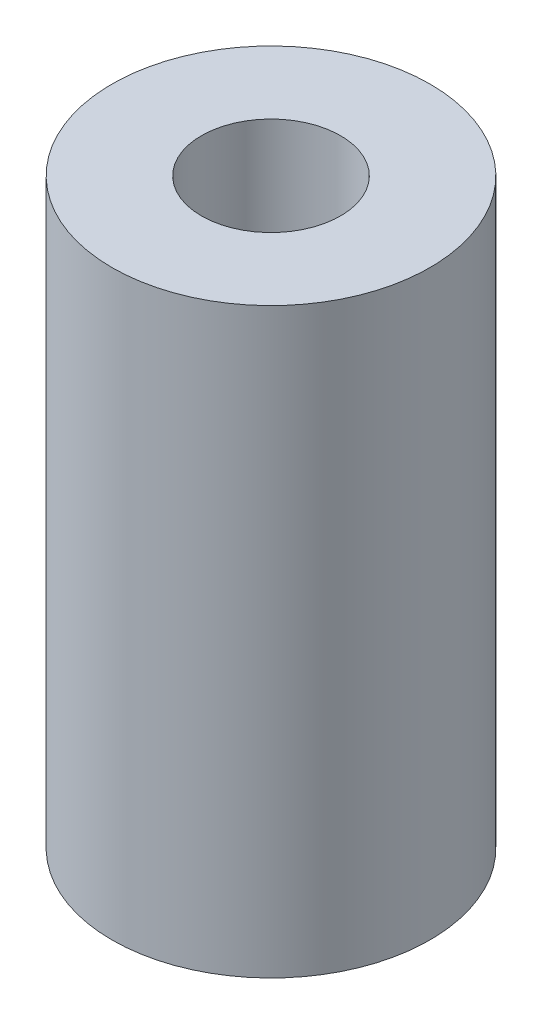
SolidWorks part; units mm, degrees
ref_plane "前视基准面" through (0, 0, 0) normal (0, 0, 1) x (1, 0, 0)
ref_plane "上视基准面" through (0, 0, 0) normal (0, 1, 0) x (1, 0, 0)
ref_plane "右视基准面" through (0, 0, 0) normal (1, 0, 0) x (0, 0, -1)
other "Configuration Table"
sketch "草图1" plane through (0, 0, 0) normal (0, 1, 0) x (1, 0, 0)
  circle A0 centre (0, 0) radius 1.75
  circle A1 centre (0, 0) radius 4
  dimension "D1" = 3.5
  dimension "D2" = 8
extrude "凸台-拉伸1" add sketch "草图1" along normal blind 14.65
